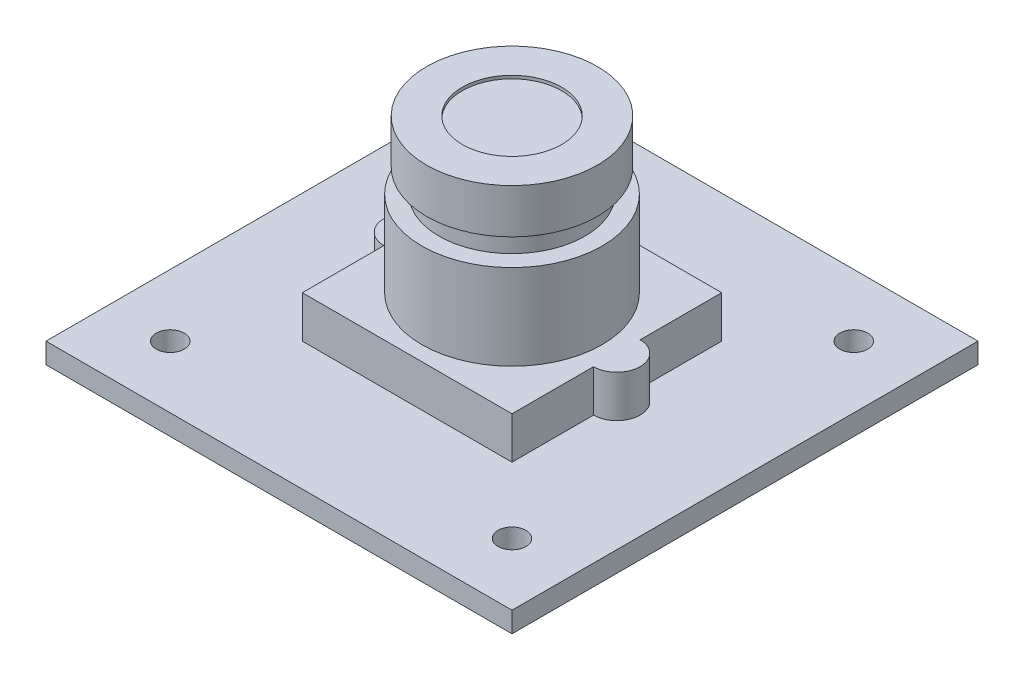
SolidWorks part; units mm, degrees
ref_plane "Front" through (0, 0, 0) normal (0, 0, 1) x (1, 0, 0)
ref_plane "Top" through (0, 0, 0) normal (0, 1, 0) x (1, 0, 0)
ref_plane "Right" through (0, 0, 0) normal (1, 0, 0) x (0, 0, -1)
sketch "Sketch1" plane through (0, 0, 0) normal (0, 1, 0) x (1, 0, 0)
  line L1 (-19.05, -19.05) -> (19.05, -19.05)
  line L2 (-19.05, -19.05) -> (-19.05, 19.05)
  line L3 (-19.05, 19.05) -> (19.05, 19.05)
  line L4 (19.05, -19.05) -> (19.05, 19.05)
  line L5 (-19.05, -19.05) -> (19.05, 19.05) construction
  line L6 (-19.05, 19.05) -> (19.05, -19.05) construction
  line L7 (-13.97, 13.97) -> (13.97, 13.97) construction
  line L8 (-13.97, 13.97) -> (-13.97, -13.97) construction
  line L9 (-13.97, -13.97) -> (13.97, -13.97) construction
  line L10 (13.97, 13.97) -> (13.97, -13.97) construction
  line L11 (-13.97, 13.97) -> (13.97, -13.97) construction
  line L12 (-13.97, -13.97) -> (13.97, 13.97) construction
  circle A0 centre (-13.97, 13.97) radius 1.143
  circle A1 centre (-13.97, -13.97) radius 1.143
  circle A2 centre (13.97, -13.97) radius 1.143
  circle A3 centre (13.97, 13.97) radius 1.143
  point P0 (0, 0)
  point P6 (0, 0)
  dimension "D5" = 2.286
  dimension "D1" = 38.1
  dimension "D2" = 38.1
  dimension "D3" = 27.94
  dimension "D4" = 27.94
extrude "Boss-Extrude1" add sketch "Sketch1" along normal blind 1.6764
sketch "Sketch2" plane through (0, 1.6764, 0) normal (0, 1, 0) x (1, 0, 0)
  line L0 (-8.5725, -1.905) -> (-8.5725, -8.5725)
  line L1 (-8.5725, 8.5725) -> (8.5725, 8.5725)
  line L2 (-8.5725, 8.5725) -> (-8.5725, 1.905)
  line L3 (-8.5725, -8.5725) -> (8.5725, -8.5725)
  line L4 (8.5725, 8.5725) -> (8.5725, 1.905)
  line L5 (-8.5725, 8.5725) -> (8.5725, -8.5725) construction
  line L6 (-8.5725, -8.5725) -> (8.5725, 8.5725) construction
  line L7 (8.5725, -1.905) -> (8.5725, -8.5725)
  line L8 (-8.5725, 1.905) -> (8.5725, 1.905) construction
  line L9 (8.5725, -1.905) -> (-8.5725, -1.905) construction
  line L10 (-10.4775, 0) -> (0, 0) construction
  arc A0 (-8.5725, 1.905) -> (-8.5725, -1.905) centre (-8.5725, 0) ccw
  arc A1 (8.5725, -1.905) -> (8.5725, 1.905) centre (8.5725, 0) ccw
  point P0 (0, 0)
  dimension "D3" = 3.81
  dimension "D1" = 17.145
  dimension "D2" = 17.145
extrude "Boss-Extrude2" add sketch "Sketch2" along normal blind 3.429
sketch "Sketch3" plane through (0, 5.1054, 0) normal (0, 1, 0) x (1, 0, 0)
  circle A0 centre (0, 0) radius 7.366
  dimension "D1" = 14.732
extrude "Boss-Extrude3" add sketch "Sketch3" along normal blind 6.985
sketch "Sketch4" plane through (0, 12.0904, 0) normal (0, 1, 0) x (1, 0, 0)
  circle A0 centre (0, 0) radius 5.969
  dimension "D1" = 11.938
extrude "Boss-Extrude4" add sketch "Sketch4" along normal blind 1.905
sketch "Sketch5" plane through (0, 13.9954, 0) normal (0, 1, 0) x (1, 0, 0)
  circle A0 centre (0, 0) radius 6.985
  dimension "D1" = 13.97
extrude "Boss-Extrude5" add sketch "Sketch5" along normal blind 3.6322
sketch "Sketch6" plane through (0, 17.6276, 0) normal (0, 1, 0) x (1, 0, 0)
  circle A0 centre (0, 0) radius 4.064
  dimension "D1" = 8.128
extrude "Cut-Extrude1" cut sketch "Sketch6" against normal blind 0.254
sketch "Sketch7" plane through (0, 0, 0) normal (0, -1, 0) x (1, 0, 0)
  line L0 (19.05, -19.05) -> (-19.05, -19.05) construction
  line L1 (-1.27, -11.0236) -> (-11.303, -11.0236)
  line L2 (-1.27, -11.0236) -> (-1.27, -15.748)
  line L3 (-1.27, -15.748) -> (-11.303, -15.748)
  line L4 (-11.303, -11.0236) -> (-11.303, -15.748)
  line L5 (-19.05, -19.05) -> (-19.05, 19.05) construction
  line L6 (-1.905, -11.6586) -> (-1.905, -15.113)
  line L7 (-1.905, -15.113) -> (-10.668, -15.113)
  line L8 (-10.668, -11.6586) -> (-10.668, -15.113)
  line L9 (-1.905, -11.6586) -> (-10.668, -11.6586)
  dimension "D1" = 3.302
  dimension "D2" = 4.7244
  dimension "D3" = 10.033
  dimension "D4" = 7.747
  dimension "D5" = 0.635
extrude "Boss-Extrude6" add sketch "Sketch7" along normal blind 6.604
sketch "Sketch9" plane through (0, 0, -11.0236) normal (0, 0, 1) x (1, 0, 0)
  line L0 (-6.2865, -6.604) -> (-6.2865, 0) construction
  line L1 (-1.27, -6.604) -> (-11.303, -6.604) construction
  line L2 (-1.27, 0) -> (-11.303, 0) construction
  line L4 (-4.699, 0) -> (-7.874, 0)
  line L5 (-4.699, 0) -> (-4.699, -6.604)
  line L6 (-4.699, -6.604) -> (-7.874, -6.604)
  line L7 (-7.874, 0) -> (-7.874, -6.604)
  line L8 (-4.699, 0) -> (-7.874, -6.604) construction
  line L9 (-4.699, -6.604) -> (-7.874, 0) construction
  point P6 (-6.2865, -3.302)
  dimension "D1" = 3.175
extrude "Cut-Extrude2" cut sketch "Sketch9" against normal up to next
